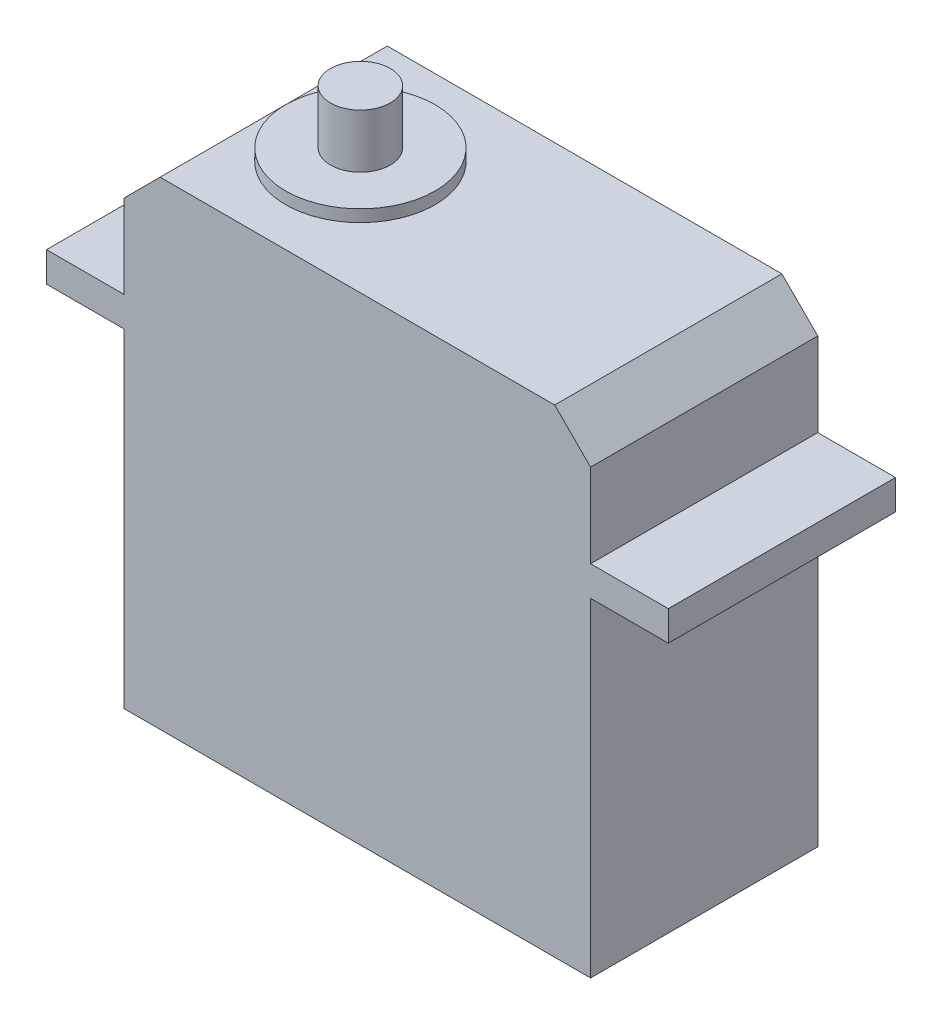
SolidWorks part; units mm, degrees
material "Nylon 6/10"
ref_plane "Front Plane" through (0, 0, 0) normal (0, 0, 1) x (1, 0, 0)
ref_plane "Top Plane" through (0, 0, 0) normal (0, 1, 0) x (1, 0, 0)
ref_plane "Right Plane" through (0, 0, 0) normal (1, 0, 0) x (0, 0, -1)
sketch "Sketch1" plane through (0, 0, 0) normal (0, 1, 0) x (1, 0, 0)
  line L1 (0, 0) -> (39, 0)
  line L2 (0, 0) -> (0, 19)
  line L3 (0, 19) -> (39, 19)
  line L4 (39, 0) -> (39, 19)
  dimension "D1" = 39
  dimension "D2" = 19
extrude "Boss-Extrude1" add sketch "Sketch1" along normal blind 40
sketch "Sketch2" plane through (39, 0, 0) normal (1, 0, 0) x (0, 0, -1)
  line L0 (0, 40) -> (0, 0) construction
  line L1 (0, 27.5) -> (19, 27.5)
  line L2 (0, 27.5) -> (0, 30)
  line L3 (0, 30) -> (19, 30)
  line L4 (19, 27.5) -> (19, 30)
  line L5 (19, 40) -> (19, 0) construction
  dimension "D1" = 2.5
  dimension "D2" = 27.5
extrude "Boss-Extrude2" add sketch "Sketch2" along normal blind 6.5
sketch "Sketch3" plane through (0, 0, 0) normal (-1, 0, 0) x (0, 0, 1)
  line L0 (-19, 40) -> (-19, 0) construction
  line L1 (-19, 27.5) -> (0, 27.5)
  line L2 (-19, 27.5) -> (-19, 30)
  line L3 (-19, 30) -> (0, 30)
  line L4 (0, 27.5) -> (0, 30)
  line L5 (0, 40) -> (0, 0) construction
  dimension "D1" = 2.5
  dimension "D2" = 27.5
extrude "Boss-Extrude3" add sketch "Sketch3" along normal blind 6.5
sketch "Sketch4" plane through (0, 40, 0) normal (0, 1, 0) x (1, 0, 0)
  line L0 (0, 19) -> (0, 0) construction
  circle A0 centre (10.25, 9.5) radius 6.25
  point P4 (0, 9.5)
  dimension "D1" = 12.5
  dimension "D2" = 0
  dimension "D3" = 10.25
extrude "Boss-Extrude4" add sketch "Sketch4" along normal blind 1
sketch "Sketch5" plane through (0, 41, 0) normal (0, 1, 0) x (1, 0, 0)
  circle A0 centre (10.25, 9.5) radius 2.5
  dimension "D1" = 5
extrude "Boss-Extrude5" add sketch "Sketch5" along normal blind 4.5 contours A0
chamfer "Chamfer1" distance 3 angle 45 1 edges at (0, 40, -9.5)
chamfer "Chamfer2" distance 3 1 edges at (39, 40, -9.5)
